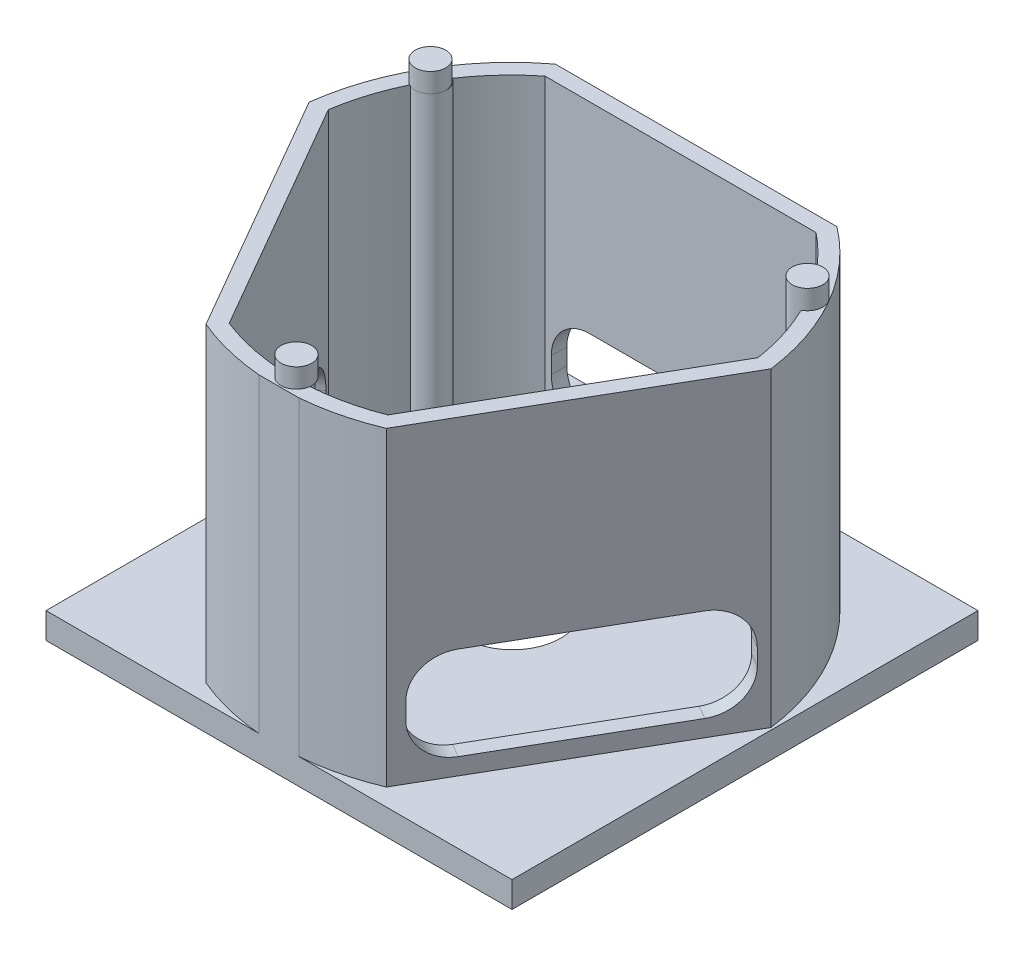
SolidWorks part; units mm, degrees
ref_plane "Front Plane" through (0, 0, 0) normal (0, 0, 1) x (1, 0, 0)
ref_plane "Top Plane" through (0, 0, 0) normal (0, 1, 0) x (1, 0, 0)
ref_plane "Right Plane" through (0, 0, 0) normal (1, 0, 0) x (0, 0, -1)
sketch "Sketch1" plane through (0, 0, 0) normal (0, 1, 0) x (1, 0, 0)
  line L0 (-46.0375, 60.4998) -> (46.0375, 60.4998)
  line L1 (-76.2, 76.0776) -> (76.2, 76.0776)
  line L2 (-76.2, 76.0776) -> (-76.2, -76.3224)
  line L3 (-76.2, -76.3224) -> (76.2, -76.3224)
  line L4 (76.2, 76.0776) -> (76.2, -76.3224)
  line L5 (-25.9539, -66.2534) -> (-70.2481, 10.4664)
  line L6 (75.5191, 9.4361) -> (29.4816, -70.3032)
  line L7 (-29.4816, -70.3032) -> (-75.5191, 9.4361)
  line L8 (70.2481, 10.4664) -> (25.9539, -66.2534)
  line L9 (-44.2942, 55.4198) -> (44.2942, 55.4198)
  arc A0 (-29.4816, -70.3032) -> (29.4816, -70.3032) centre (0, -0.1224) ccw
  arc A1 (75.5191, 9.4361) -> (46.0375, 60.4998) centre (0, -0.1224) ccw
  arc A2 (-46.0375, 60.4998) -> (-75.5191, 9.4361) centre (0, -0.1224) ccw
  arc A3 (-44.2942, 55.4198) -> (-70.2481, 10.4664) centre (0, -0.1224) ccw
  arc A4 (-25.9539, -66.2534) -> (25.9539, -66.2534) centre (0, -0.1224) ccw
  arc A5 (70.2481, 10.4664) -> (44.2942, 55.4198) centre (0, -0.1224) ccw
  circle A6 centre (-61.5239, 35.3984) radius 5.0069
  circle A7 centre (61.5239, 35.3984) radius 5.0069
  circle A8 centre (0, -71.164) radius 5.0069
  point P0 (0, -0.1224)
  point P16 (0, -0.1224)
  point P28 (0, -0.1224)
  point P29 (0, -0.1224)
  dimension "D3" = 10.0139
  dimension "D4" = 76.1217
  dimension "D5" = 71.0417
  dimension "D1" = 152.4
  dimension "D2" = 92.075
  dimension "D6" = 25.9539
  dimension "D7" = 29.4816
  dimension "D8" = 44.2942
  dimension "D9" = 9.4361
  dimension "D10" = 76.0776
  dimension "D12" = 76.2
extrude "Boss-Extrude1" add sketch "Sketch1" along normal blind 8.4667 contours L4 L1 L2 L3 A2 L0 A1 L6 A0 L7 | L0 A2 L7 A0 L6 A1 A8 A4 L5 A3 A6 L9 A5 A7 L8 | A8 A4 L8 A5 A7 L9 A3 A6 L5 | A3 A6 | A3 A6 | A5 A7 | A5 A7 | A4 A8 | A4 A8
sketch "Sketch3" plane through (0, 8.4667, 0) normal (0, 1, 0) x (1, 0, 0)
  line L0 (-46.0871, 60.1423) -> (45.9879, 60.1423)
  line L1 (-26.0034, -66.611) -> (-70.2976, 10.1088)
  line L2 (75.4696, 9.0786) -> (29.4321, -70.6607)
  line L3 (-29.5312, -70.6607) -> (-75.5687, 9.0786)
  line L4 (70.1985, 10.1088) -> (25.9043, -66.611)
  line L5 (-44.3438, 55.0623) -> (44.2447, 55.0623)
  line L6 (76.2, 76.0776) -> (76.2, -76.3224) construction
  arc A0 (-29.5312, -70.6607) -> (29.4321, -70.6607) centre (-0.0496, -0.4799) ccw
  arc A1 (75.4696, 9.0786) -> (45.9879, 60.1423) centre (-0.0496, -0.4799) ccw
  arc A2 (-46.0871, 60.1423) -> (-75.5687, 9.0786) centre (-0.0496, -0.4799) ccw
  arc A3 (-44.3438, 55.0623) -> (-70.2976, 10.1088) centre (-0.0496, -0.4799) ccw
  arc A4 (-26.0034, -66.611) -> (25.9043, -66.611) centre (-0.0496, -0.4799) ccw
  arc A5 (70.1985, 10.1088) -> (44.2447, 55.0623) centre (-0.0496, -0.4799) ccw
  circle A6 centre (-61.5734, 35.0409) radius 5.0069
  circle A7 centre (61.4743, 35.0409) radius 5.0069
  circle A8 centre (-0.0496, -71.5216) radius 5.0069
  point P0 (-0.0496, -0.4799)
  point P12 (-0.0496, -0.4799)
  point P24 (-0.0496, -0.4799)
  point P25 (-0.0496, -0.4799)
  line M16 (-76.2, -76.3224) -> (76.2, -76.3224)
  dimension "D2" = 10.0139
  dimension "D3" = 76.1217
  dimension "D4" = 71.0417
  dimension "D1" = 92.075
  dimension "D5" = 0.7304
  dimension "D6" = 6.0015
  dimension "D7" = 14.7257
  dimension "D8" = 30.2121
  dimension "D9" = 15.9353
extrude "Boss-Extrude3" add sketch "Sketch3" along normal blind 101.6 contours A3 A6 | A3 A6 | A8 A0 L2 A1 L0 A2 L3 A4 L1 A3 A6 L5 A5 A7 L4 M16 | A4 A8 | A8 A4 M16 | A5 A7 | A5 A7
sketch "Sketch4" plane through (0, 110.0667, 0) normal (0, 1, 0) x (1, 0, 0)
  circle A0 centre (61.4743, 35.0409) radius 5.0069
  circle A1 centre (0.1284, -70.7597) radius 5.0069
  circle A2 centre (-61.6011, 34.8176) radius 5.0069
  point P10 (0, 0)
  dimension "D2" = 10.0139
  dimension "D3" = 8.6966
  dimension "D4" = 70.2976
  dimension "D5" = 70.426
  dimension "D1" = 3
extrude "Boss-Extrude4" add sketch "Sketch4" along normal blind 6.35
sketch "Sketch6" plane through (-52.7454, 0, 30.4526) normal (-0.866, 0, 0.5) x (0.5, 0, 0.866)
  line L0 (0.3909, 8.4667) -> (0.3909, 13.9382)
  line L1 (46.4284, 8.4667) -> (-45.6466, 8.4667) construction
  line L2 (-41.7992, 13.9382) -> (42.3383, 13.9382)
  line L3 (-41.7992, 13.9382) -> (-41.7992, 44.406)
  line L4 (-41.7992, 44.406) -> (42.3383, 44.406)
  line L5 (42.3383, 44.406) -> (42.3383, 13.9382)
  point P8 (0.3909, 11.2024)
  dimension "D1" = 84.1375
  dimension "D2" = 30.4678
  dimension "D3" = 2.7358
extrude "Cut-Extrude1" cut sketch "Sketch6" against normal up to next contours L5 L4 L3 L2
sketch "Sketch7" plane through (0, 0, 0) normal (1, 0, 0) x (0, 0, -1)
  line L0 (0, 0) -> (0, 119.95) construction
fillet "Fillet1" radius 12.54 4 edges at (-29.3765, 44.406, 65.8486) (-29.3765, 13.9382, 65.8486) (-71.4453, 44.406, -7.0166) (-71.4453, 13.9382, -7.0166)
pattern_circular "CirPattern3" count 3 every 120 about axis through (0, 0, 0) along (0, 1, 0) of "Fillet1", "Cut-Extrude1"
sketch "Sketch8" plane through (0, 0, 0) normal (0, -1, 0) x (-1, 0, 0)
  line L0 (0, 0) -> (0, -83.4011) construction
  line L1 (0, 0) -> (-128.2552, 0) construction
  line L2 (38.1, -76.3224) -> (38.1, 76.0776) construction
  line L3 (76.2, -76.3224) -> (-76.2, -76.3224) construction
  line L4 (76.2, 76.0776) -> (-76.2, 76.0776) construction
  line L5 (76.2, -63.6224) -> (-76.2, -63.6224) construction
  line L6 (76.2, 76.0776) -> (76.2, -76.3224) construction
  line L7 (-76.2, 76.0776) -> (-76.2, -76.3224) construction
  line L8 (63.5, -76.3224) -> (63.5, 76.0776) construction
  line L9 (76.2, -38.2224) -> (-76.2, -38.2224) construction
  line L10 (-76.2, 37.9776) -> (76.2, 37.9776) construction
  line L11 (-38.1, -76.3224) -> (-38.1, 76.0776) construction
  line L12 (-63.5, -76.3224) -> (-63.5, 76.0776) construction
  line L13 (-76.2, 63.3776) -> (76.2, 63.3776) construction
  line L14 (76.2, 76.0776) -> (-76.2, 76.0776) construction
  circle A0 centre (63.5, -38.2224) radius 3.175
  circle A1 centre (38.1, -63.6224) radius 3.175
  circle A2 centre (-63.5, -38.2224) radius 3.175
  circle A3 centre (-38.1, -63.6224) radius 3.175
  circle A8 centre (63.5, 37.9776) radius 3.175
  circle A9 centre (38.1, 63.3776) radius 3.175
  circle A10 centre (-38.1, 63.3776) radius 3.175
  circle A11 centre (-63.5, 37.9776) radius 3.175
  dimension "D5" = 6.35
  dimension "D6" = 6.35
  dimension "D8" = 6.35
  dimension "D10" = 6.35
  dimension "D11" = 6.35
  dimension "D12" = 6.35
  dimension "D1" = 12.7
  dimension "D2" = 38.1
  dimension "D3" = 12.7
  dimension "D4" = 38.1
  dimension "D7" = 38.1
  dimension "D9" = 12.7
extrude "Cut-Extrude2" cut sketch "Sketch8" against normal blind 6.35
sketch "Sketch9" plane through (0, 8.4667, 0) normal (0, 1, 0) x (1, 0, 0)
  circle A0 centre (0, 0) radius 15.793
extrude "Cut-Extrude4" cut sketch "Sketch9" against normal through all
